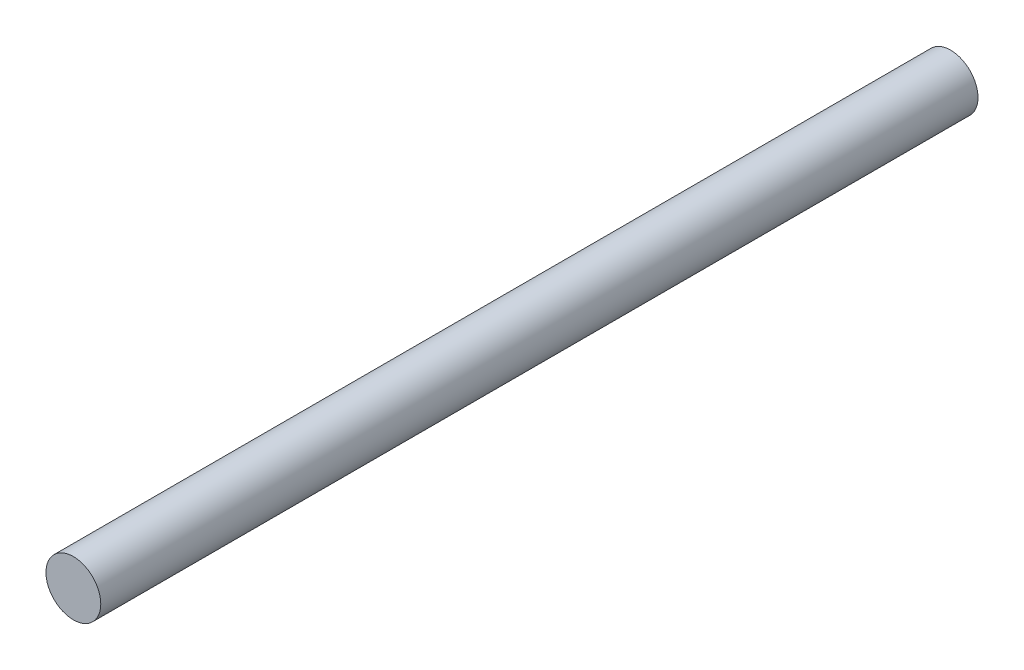
SolidWorks part; units mm, degrees
ref_plane "前视基准面" through (0, 0, 0) normal (0, 0, 1) x (1, 0, 0)
ref_plane "上视基准面" through (0, 0, 0) normal (0, 1, 0) x (1, 0, 0)
ref_plane "右视基准面" through (0, 0, 0) normal (1, 0, 0) x (0, 0, -1)
sketch "草图1" plane through (0, 0, 0) normal (0, 0, 1) x (1, 0, 0)
  circle A0 centre (0, 0) radius 2.5
  dimension "D1" = 5
extrude "凸台-拉伸1" add sketch "草图1" along normal blind 80
